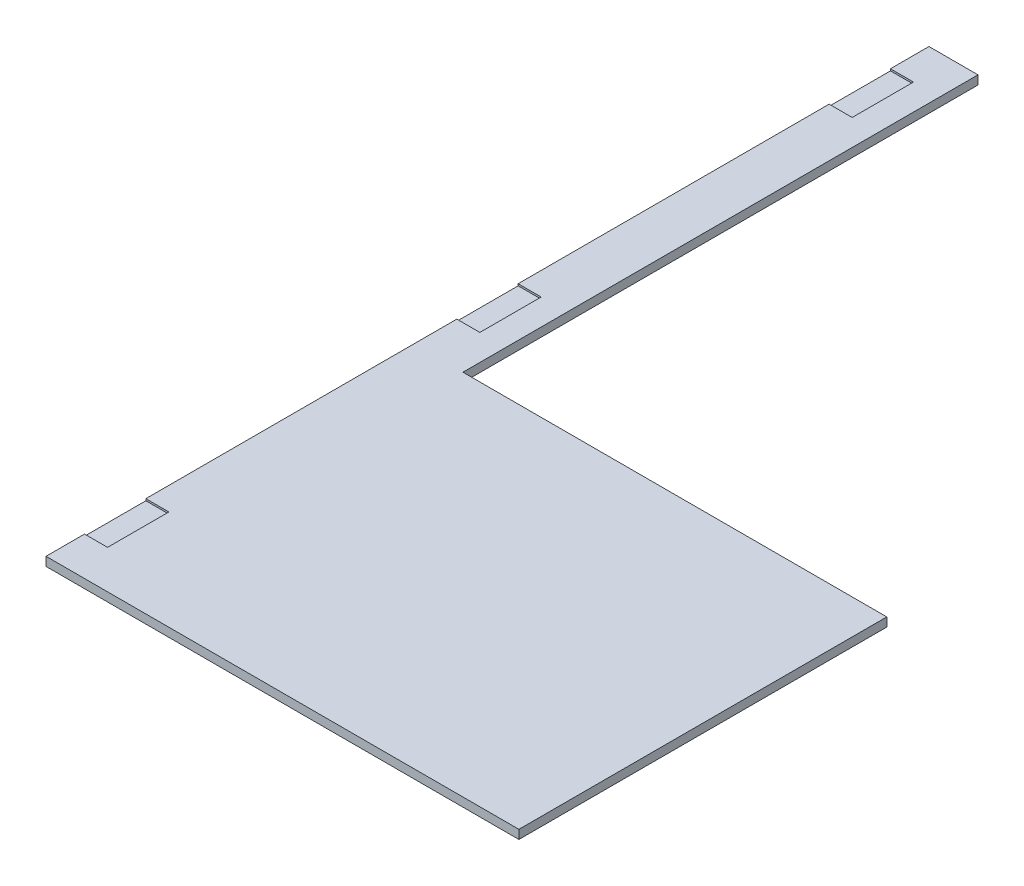
SolidWorks part; units mm, degrees
ref_plane "Front Plane" through (0, 0, 0) normal (0, 0, 1) x (1, 0, 0)
ref_plane "Top Plane" through (0, 0, 0) normal (0, 1, 0) x (1, 0, 0)
ref_plane "Right Plane" through (0, 0, 0) normal (1, 0, 0) x (0, 0, -1)
sketch "Sketch1" plane through (0, 0, 0) normal (0, 1, 0) x (1, 0, 0)
  line L0 (-489.7438, 381) -> (-489.7438, 1447.8)
  line L1 (-489.7438, -381) -> (489.7437, -381)
  line L2 (-489.7438, -381) -> (-489.7438, 381)
  line L4 (489.7437, -381) -> (489.7437, 381)
  line L5 (-489.7438, -381) -> (489.7437, 381) construction
  line L6 (-489.7438, 381) -> (489.7437, -381) construction
  line L7 (-489.7438, 1447.8) -> (-388.1438, 1447.8)
  line L8 (-388.1438, 1447.8) -> (-388.1438, 381)
  line L9 (489.7437, 381) -> (-388.1438, 381)
  point P0 (0, 0)
  dimension "D1" = 762
  dimension "D2" = 979.4875
  dimension "D3" = 101.6
  dimension "D4" = 1066.8
extrude "Boss-Extrude1" add sketch "Sketch1" along normal blind 18.2562
sketch "Sketch2" plane through (0, 18.2562, 0) normal (0, 1, 0) x (1, 0, 0)
  line L0 (-489.7438, 1368.0272) -> (-441.9918, 1368.0272)
  line L1 (-489.7438, 1447.8) -> (-489.7438, -381) construction
  line L2 (-441.9918, 1368.0272) -> (-441.9918, 1241.0272)
  line L3 (-441.9918, 1241.0272) -> (-489.7438, 1241.0272)
  line L4 (-489.7438, 1368.0272) -> (-489.7438, 1241.0272)
  line L5 (-489.7437, 596.9) -> (-489.7437, 469.9)
  line L6 (-441.9917, 469.9) -> (-489.7437, 469.9)
  line L7 (-441.9917, 596.9) -> (-441.9917, 469.9)
  line L8 (-489.7437, 596.9) -> (-441.9917, 596.9)
  line L9 (-489.7438, -174.2272) -> (-489.7438, -301.2272)
  line L10 (-441.9917, -301.2272) -> (-489.7438, -301.2272)
  line L11 (-441.9917, -174.2272) -> (-441.9917, -301.2272)
  line L12 (-489.7438, -174.2272) -> (-441.9917, -174.2272)
  line L13 (-465.8678, 1368.0272) -> (-465.8678, 1447.8) construction
  line L14 (-388.1438, 1447.8) -> (-489.7438, 1447.8) construction
  line L15 (-465.8678, -301.2272) -> (-465.8678, -381) construction
  line L16 (-489.7438, -381) -> (489.7437, -381) construction
  line L17 (-465.8678, 1241.0272) -> (-465.8677, 596.9) construction
  line L18 (-465.8677, -174.2272) -> (-465.8678, 469.9) construction
  dimension "D2" = 47.752
  dimension "D3" = 127
  dimension "D1" = 3
extrude "Cut-Extrude1" cut sketch "Sketch2" against normal blind 3.81
